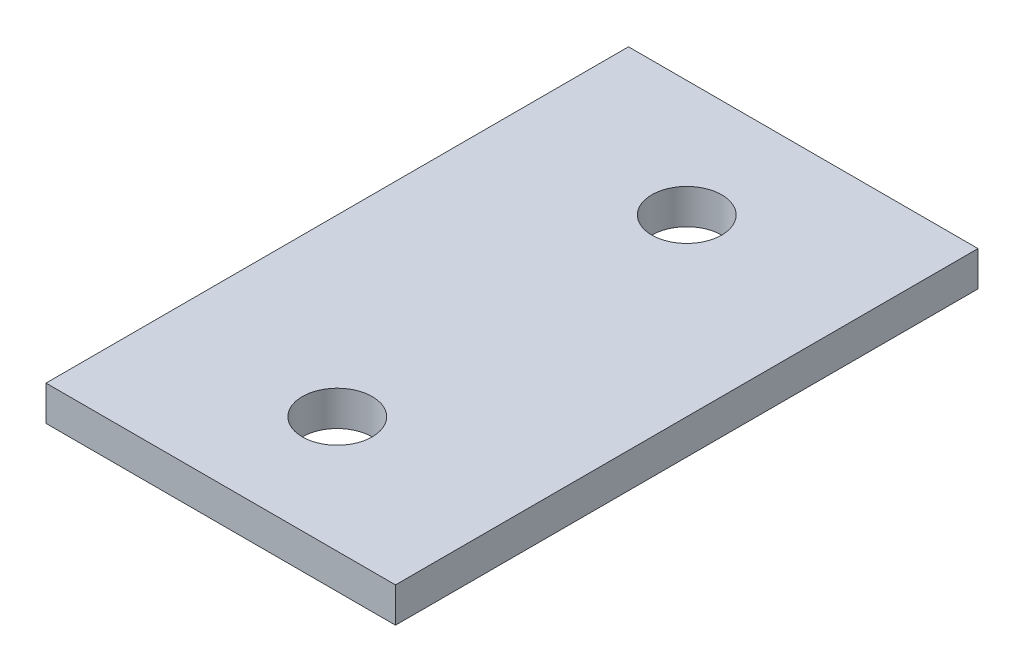
SolidWorks part; units mm, degrees
material "1023 Chapa de acero al carbono (SS)"
ref_plane "Alzado" through (0, 0, 0) normal (0, 0, 1) x (1, 0, 0)
ref_plane "Planta" through (0, 0, 0) normal (0, 1, 0) x (1, 0, 0)
ref_plane "Vista lateral" through (0, 0, 0) normal (1, 0, 0) x (0, 0, -1)
sketch "Croquis1" plane through (0, 0, 0) normal (0, 1, 0) x (1, 0, 0)
  line L1 (-7.5, 12.5) -> (7.5, 12.5)
  line L2 (-7.5, 12.5) -> (-7.5, -12.5)
  line L3 (-7.5, -12.5) -> (7.5, -12.5)
  line L4 (7.5, 12.5) -> (7.5, -12.5)
  line L5 (-7.5, 12.5) -> (7.5, -12.5) construction
  line L6 (-7.5, -12.5) -> (7.5, 12.5) construction
  point P0 (0, 0)
  dimension "D1" = 25
  dimension "D2" = 15
extrude "Saliente-Extruir2" add sketch "Croquis1" along normal blind 2
sketch "Croquis2" plane through (0, 2, 0) normal (0, 1, 0) x (1, 0, 0)
  circle A0 centre (0, 7.5) radius 1.5
  circle A1 centre (0, -7.5) radius 1.5
  dimension "D1" = 7.5
  dimension "D2" = 7.5
extrude "Cortar-Extruir1" cut sketch "Croquis2" against normal blind 2
sketch "Croquis3" plane through (0, 2, 0) normal (0, 1, 0) x (1, 0, 0)
  line L1 (13.3056, -19.5494) -> (-13.3056, -19.5494)
  line L2 (13.3056, -19.5494) -> (13.3056, 19.5494)
  line L3 (13.3056, 19.5494) -> (-13.3056, 19.5494)
  line L4 (-13.3056, -19.5494) -> (-13.3056, 19.5494)
  line L5 (13.3056, -19.5494) -> (-13.3056, 19.5494) construction
  line L6 (13.3056, 19.5494) -> (-13.3056, -19.5494) construction
  point P0 (0, 0)
extrude "Cortar-Extruir2" cut sketch "Croquis3" against normal blind 0.5
